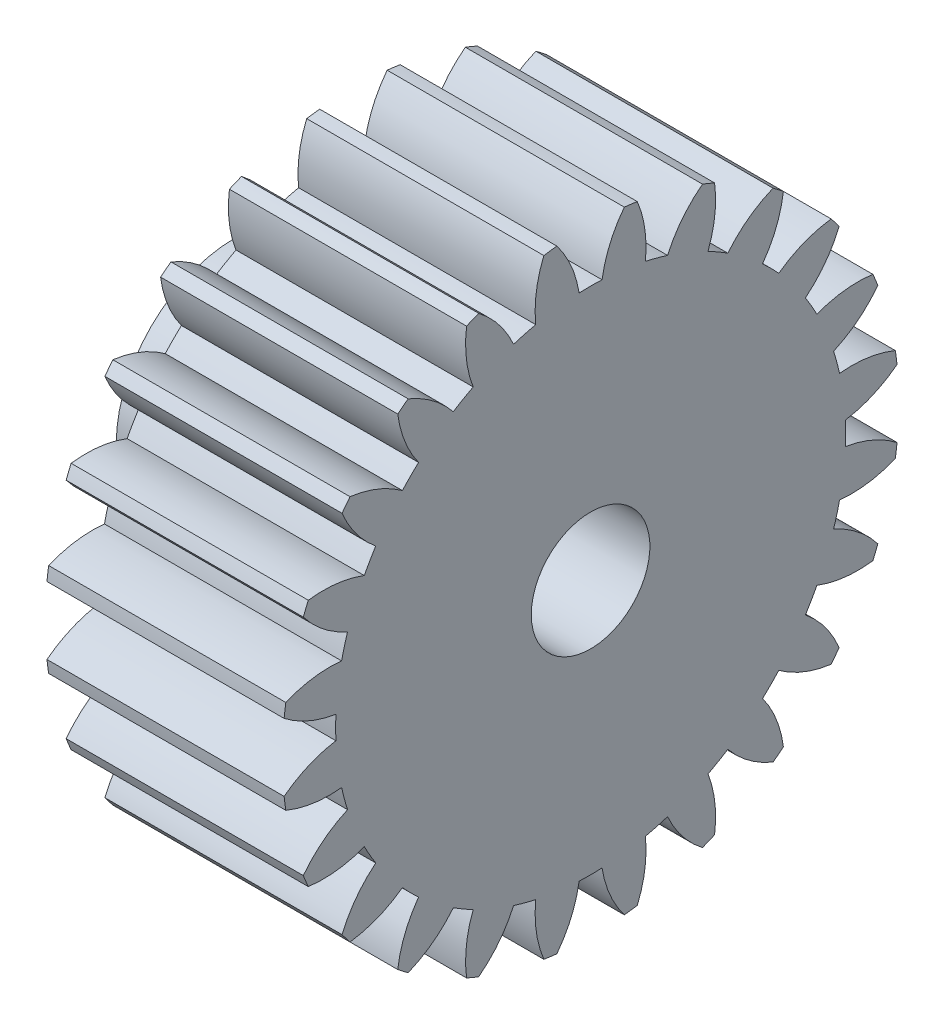
SolidWorks part; units mm, degrees
ref_plane "Plane1" through (0, 0, 0) normal (0, 0, 1) x (1, 0, 0)
ref_plane "Plane2" through (0, 0, 0) normal (0, 1, 0) x (1, 0, 0)
ref_plane "Plane3" through (0, 0, 0) normal (1, 0, 0) x (0, 0, -1)
sketch "HoldingSke" plane through (0, 0, 0) normal (0, 1, 0) x (1, 0, 0)
  line L0 (0, 0) -> (0.9135, -0.4067)
  line L1 (-15, 0) -> (100, 0) construction
  line L2 (0, 0) -> (-2.1039, 2.3779)
  line L3 (0, 0) -> (-11.863, 4.5341)
  line L4 (0, 0) -> (7.8894, 3.5126)
  line L5 (0, 0) -> (-14.0543, -5.2418)
  line L6 (0, 0) -> (-8.2896, -5.593)
  line L7 (-2.1039, 2.3779) -> (1.1249, 17.0263)
  line L8 (-76.2, 54.61) -> (-75.3, 54.61)
  line L9 (-71.009, 38.7566) -> (-53.1078, 45.2721)
  line L10 (-76.2, 71.12) -> (104.1128, 71.12)
  line L11 (0, 0) -> (-10, 0)
  line L12 (-76.2, 101.6) -> (-76.162, 101.6)
  line L13 (24.9733, 27.94) -> (52.9518, 28.4284)
  line L14 (24.9733, 27.94) -> (24.9743, 27.94)
  line L15 (24.9733, 27.94) -> (100.4006, 29.5858)
  line L16 (-63.627, -1) -> (-12.827, -1)
  circle A0 centre (0, 0) radius 2.5
  circle A1 centre (0, 0) radius 5
  circle A2 centre (0, 0) radius 5
  circle A3 centre (0, 0) radius 2.5
  dimension "MHD" = 10
  dimension "Hub_dia" = 10
  dimension "Bore" = 5
  dimension "MBD" = 5
  dimension "Num_teeth" = 24
  dimension "Pitch" = 1
  dimension "Overall_len" = 15
  dimension "Show_teeth" = 24
  dimension "Thickness" = 10
  dimension "OAL" = 15.0001
  dimension "T_dim" = 0.9
  dimension "Ap" = 20
  dimension "H" = 19.05
  dimension "Pitch_radius" = 180.3128
  dimension "Width" = 10
  dimension "Backlash" = 0.038
  dimension "Addendum_fac" = 1
  dimension "Dedendum_fac" = 1.25
  dimension "Clearance_fac" = 0.25
  dimension "Dedendum_add" = 0.001
  dimension "Module" = 1
sketch "BasProSke" plane through (0, 0, 0) normal (0, 1, 0) x (1, 0, 0)
  line L0 (-10, 0) -> (60, 0) construction
  line L1 (0, 0) -> (0, 13)
  line L2 (0, 0) -> (10, 0)
  line L3 (10, 0) -> (10, 13)
  line L4 (10, 13) -> (0, 13)
  dimension "Thickness" = 10
  dimension "Diameter" = 26
revolve "Base-Revolve" add sketch "BasProSke" angle 360 about L0
sketch "TooCutSke" plane through (0, 0, 0) normal (1, 0, 0) x (0, 0, -1)
  line L1 (0, 0) -> (0, 107) construction
  line L2 (0, 0) -> (-0.8513, 11.9698) construction
  line L3 (0, 0) -> (-3.127, 23.752) construction
  line L4 (-0.8513, 11.9698) -> (-1.5635, 11.876) construction
  arc A0 (0.4834, 10.7381) -> (-0.4834, 10.7381) centre (0, 0) ccw
  arc A1 (1.4409, 12.9455) -> (-1.4409, 12.9455) centre (0, 0) ccw
  circle A2 centre (0, 0) radius 12 construction
  circle A3 centre (0, 0) radius 11.2763 construction
  arc A4 (-0.4834, 10.7381) -> (-1.4409, 12.9455) centre (-5.2252, 9.9926) ccw
  arc A5 (1.4409, 12.9455) -> (0.4834, 10.7381) centre (5.2252, 9.9926) ccw
  dimension "Root_dia" = 21.498
  dimension "Overcut_dia" = 26.0508
  dimension "Pitch_dia" = 24
  dimension "Base_dia" = 22.5526
  dimension "Flank_rad" = 4.8
  dimension "Half_ang" = 7.5
  dimension "Half_CT" = 0.7183
extrude "ToothCut" cut sketch "TooCutSke" along normal through all
fillet "Breaks" [suppressed] radius 0.02
fillet "RootFillets" [suppressed] radius 0.251
pattern_circular "TeethCuts" count 24 every 15 about axis through (-10, 0, 0) along (1, 0, 0) of "ToothCut", "RootFillets", "Breaks"
sketch "HubNeaOneSke" plane through (0, 0, 0) normal (-1, 0, 0) x (0, 0, 1)
  circle A0 centre (0, 0) radius 5
  dimension "Diameter" = 10
extrude "HubNearOne" add sketch "HubNeaOneSke" along normal blind 5.0001
sketch "HubNeaBotSke" plane through (0, 0, 0) normal (-1, 0, 0) x (0, 0, 1)
  circle A0 centre (0, 0) radius 5
  dimension "Diameter" = 10
extrude "HubNearBoth" [suppressed] add sketch "HubNeaBotSke" along normal blind 2.5
ref_plane "FarPln" through (10, 0, 0) normal (1, 0, 0) x (0, 0, -1)
sketch "HubFarSke" plane through (10, 0, 0) normal (1, 0, 0) x (0, 0, -1)
  circle A0 centre (0, 0) radius 5
  dimension "Diameter" = 10
extrude "HubFar" [suppressed] add sketch "HubFarSke" along normal blind 2.5
sketch "BorSke" plane through (0, 0, 0) normal (1, 0, 0) x (0, 0, -1)
  circle A0 centre (0, 0) radius 2.5
  dimension "Diameter" = 5
extrude "Bore" cut sketch "BorSke" along normal mid plane 30.0001
sketch "KeySke" plane through (0, 0, 0) normal (1, 0, 0) x (0, 0, -1)
  line L0 (-1, 0) -> (-1, 3.4)
  line L1 (-1, 3.4) -> (1, 3.4)
  line L2 (1, 3.4) -> (1, 0)
  line L3 (0, 0) -> (0, 34) construction
  line L4 (-1, 0) -> (1, 0)
  dimension "Offset" = 3.4
  dimension "Width" = 2
extrude "Keyway" [suppressed] cut sketch "KeySke" along normal mid plane 30.0001
pattern_circular "Keyway2" [suppressed] count 2 every 90 about axis through (-10, 0, 0) along (1, 0, 0)
equation "' \"Module@HoldingSke\" = 6.35"
equation "' \"Num_teeth@HoldingSke\" = 12"
equation "' \"Ap@HoldingSke\" =  20"
equation "' \"Ap@HoldingSke\" = 20"
equation "' \"Width@HoldingSke\" = 0.5 * 25.4"
equation "' \"Hub_dia@HoldingSke\"= 1 * 25.4"
equation "' \"Hub_dia@HoldingSke\" = 1 * 25.4"
equation "' \"Overall_len@HoldingSke\" = 1.0 * 25.4"
equation "' \"Bore@HoldingSke\" = 0.75 * 25.4"
equation "' \"T_dim@HoldingSke\" = 0.1 * 25.4"
equation "' \"Width@KeySke\" = 0.25 * 25.4"
equation "' \"Show_teeth@HoldingSke\" = 13"
equation "' \"Backlash@HoldingSke\" = 0.009 * 25.4"
equation "' \"Addendum_fac@HoldingSke\" = 1.0"
equation "' \"Dedendum_fac@HoldingSke\" = 1.25"
equation "' \"Dedendum_add@HoldingSke\" = 0.00005 * 25.4"
equation "' \"Clearance_fac@HoldingSke\" = 0.25"
equation "\"Pitch@HoldingSke\" = 1 / \"Module@HoldingSke\""
equation "\"Overcut_dia@TooCutSke\" = (\"Num_teeth@HoldingSke\" + 2 * \"Addendum_fac@HoldingSke\") / \"Pitch@HoldingSke\" + 0.002 * 25.4"
equation "\"Pitch_dia@TooCutSke\" = \"Num_teeth@HoldingSke\" / \"Pitch@HoldingSke\""
equation "\"Base_dia@TooCutSke\" = \"Num_teeth@HoldingSke\" / \"Pitch@HoldingSke\" * cos((\"Ap@HoldingSke\"  * 3.14159265 / 180))"
equation "\"Root_dia@TooCutSke\" = (\"Num_teeth@HoldingSke\" + 2) / \"Pitch@HoldingSke\" - 2 * (\"Addendum_fac@HoldingSke\" + \"Dedendum_fac@HoldingSke\") / \"Pitch@HoldingSke\" - \"Dedendum_add@HoldingSke\" * 2"
equation "\"Half_ang@TooCutSke\" = 180 / \"Num_teeth@HoldingSke\""
equation "\"Half_CT@TooCutSke\" = \"Num_teeth@HoldingSke\" / \"Pitch@HoldingSke\" * sin((3.14159265 / 2 / \"Num_teeth@HoldingSke\")) / 2 - 7 * \"Backlash@HoldingSke\" / 4"
equation "\"Flank_rad@TooCutSke\" = \"Num_teeth@HoldingSke\" / \"Pitch@HoldingSke\" / 5"
equation "\"Radius@RootFillets\" = \"Clearance_fac@HoldingSke\" / \"Pitch@HoldingSke\" + \"Dedendum_add@HoldingSke\""
equation "\"Break_rad@Breaks\" = 0.02 / \"Pitch@HoldingSke\""
equation "\"Thickness@HoldingSke\" = \"Width@HoldingSke\""
equation "\"OAL@HoldingSke\" = \"Thickness@HoldingSke\""
equation "\"MHD@HoldingSke\" = (\"Num_teeth@HoldingSke\" + 2) / \"Pitch@HoldingSke\" - 2 * (\"Addendum_fac@HoldingSke\" + \"Dedendum_fac@HoldingSke\")  / \"Pitch@HoldingSke\" - \"Dedendum_add@HoldingSke\" * 2"
equation "\"MBD@HoldingSke\" = (\"Num_teeth@HoldingSke\" + 2) / \"Pitch@HoldingSke\" - 2 * (\"Addendum_fac@HoldingSke\" + \"Dedendum_fac@HoldingSke\")  / \"Pitch@HoldingSke\" - \"Dedendum_add@HoldingSke\" * 2 - 0.002 * 25.4"
equation "\"MHD@HoldingSke\" = ((sgn( \"MHD@HoldingSke\" - \"Hub_dia@HoldingSke\" )-1)*( \"MHD@HoldingSke\" - \"Hub_dia@HoldingSke\" ))/-2+ \"Hub_dia@HoldingSke\""
equation "\"MBD@HoldingSke\" = ((sgn( \"MBD@HoldingSke\" - \"Bore@HoldingSke\" )-1)*( \"MBD@HoldingSke\" - \"Bore@HoldingSke\" ))/-2+ \"Bore@HoldingSke\""
equation "\"OAL@HoldingSke\" = ((sgn( \"OAL@HoldingSke\" - \"Overall_len@HoldingSke\" )+1)*( \"OAL@HoldingSke\" - \"Overall_len@HoldingSke\" ))/2 + \"Overall_len@HoldingSke\" + 0.000002 * 25.4"
equation "\"Num_teeth@TeethCuts\" = int( \"Show_teeth@HoldingSke\" ) + 1"
equation "\"Num_teeth@TeethCuts\" = ((sgn( \"Num_teeth@TeethCuts\" - \"Num_teeth@HoldingSke\" )-1)*( \"Num_teeth@TeethCuts\" - \"Num_teeth@HoldingSke\" ))/-2+ \"Num_teeth@HoldingSke\""
equation "\"Num_teeth@TeethCuts\" = ((sgn( \"Num_teeth@TeethCuts\" - 2.0)+1)*( \"Num_teeth@TeethCuts\" - 2.0))/2 +2.0"
equation "\"Angle@TeethCuts\" = 360.0 / \"Num_teeth@HoldingSke\""
equation "\"Diameter@BasProSke\" = (\"Num_teeth@HoldingSke\" + 2 * \"Addendum_fac@HoldingSke\") / \"Pitch@HoldingSke\""
equation "\"Thickness@BasProSke\"  = \"Thickness@HoldingSke\""
equation "' \"Fillet_rad@BasProSke\" =  \"Thickness@HoldingSke\" * 0.05"
equation "' \"Fillet_rad@BasProSke\" = \"Thickness@HoldingSke\" * 0.05"
equation "\"MHD@HoldingSke\" = ((sgn( \"MHD@HoldingSke\" - \"Root_dia@TooCutSke\" )-1)*( \"MHD@HoldingSke\" - \"Root_dia@TooCutSke\" ))/-2+ \"Root_dia@TooCutSke\""
equation "\"Diameter@HubNeaOneSke\" = \"MHD@HoldingSke\""
equation "\"Length@HubNearOne\" = \"OAL@HoldingSke\" - \"Thickness@BasProSke\""
equation "\"Diameter@HubNeaBotSke\" = \"MHD@HoldingSke\""
equation "\"Length@HubNearBoth\" = ( \"OAL@HoldingSke\" - \"Thickness@BasProSke\" ) / 2.0"
equation "\"Thickness@FarPln\" = \"Thickness@BasProSke\""
equation "\"Diameter@HubFarSke\" = \"MHD@HoldingSke\""
equation "\"Length@HubFar\" = ( \"OAL@HoldingSke\" - \"Thickness@BasProSke\" ) / 2.0"
equation "\"Diameter@BorSke\" = \"MBD@HoldingSke\""
equation "\"D1@Bore\" = \"OAL@HoldingSke\" * 2.0"
equation "\"D1@Keyway\" = \"OAL@HoldingSke\" * 2.0"
equation "\"Offset@KeySke\" = \"T_dim@HoldingSke\" + \"MBD@HoldingSke\" / 2.0"
